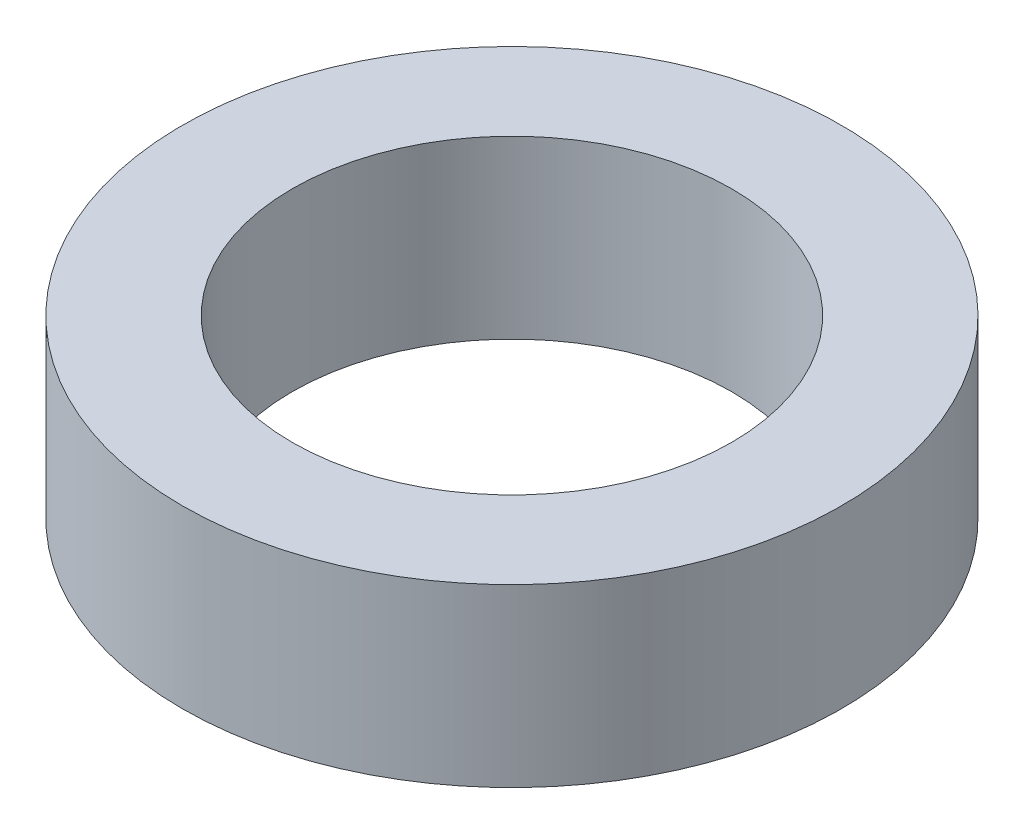
SolidWorks part; units mm, degrees
material "1023 Carbon Steel Sheet (SS)"
ref_plane "Front Plane" through (0, 0, 0) normal (0, 0, 1) x (1, 0, 0)
ref_plane "Top Plane" through (0, 0, 0) normal (0, 1, 0) x (1, 0, 0)
ref_plane "Right Plane" through (0, 0, 0) normal (1, 0, 0) x (0, 0, -1)
sketch "Sketch1" plane through (0, 0, 0) normal (0, 1, 0) x (1, 0, 0)
  circle A0 centre (0, 0) radius 5
  circle A1 centre (0, 0) radius 7.5
  dimension "D1" = 10
  dimension "D2" = 15
extrude "Boss-Extrude1" add sketch "Sketch1" along normal mid plane 4
equation "\"bearing_ID\"= 10mm"
equation "\"D1@Sketch1\"=\"bearing_ID\""
equation "\"bearingOD\"= 15mm"
equation "\"D2@Sketch1\"=\"bearingOD\""
equation "\"bearing_thickness\"= 4mm"
equation "\"D1@Boss-Extrude1\"=\"bearing_thickness\""
